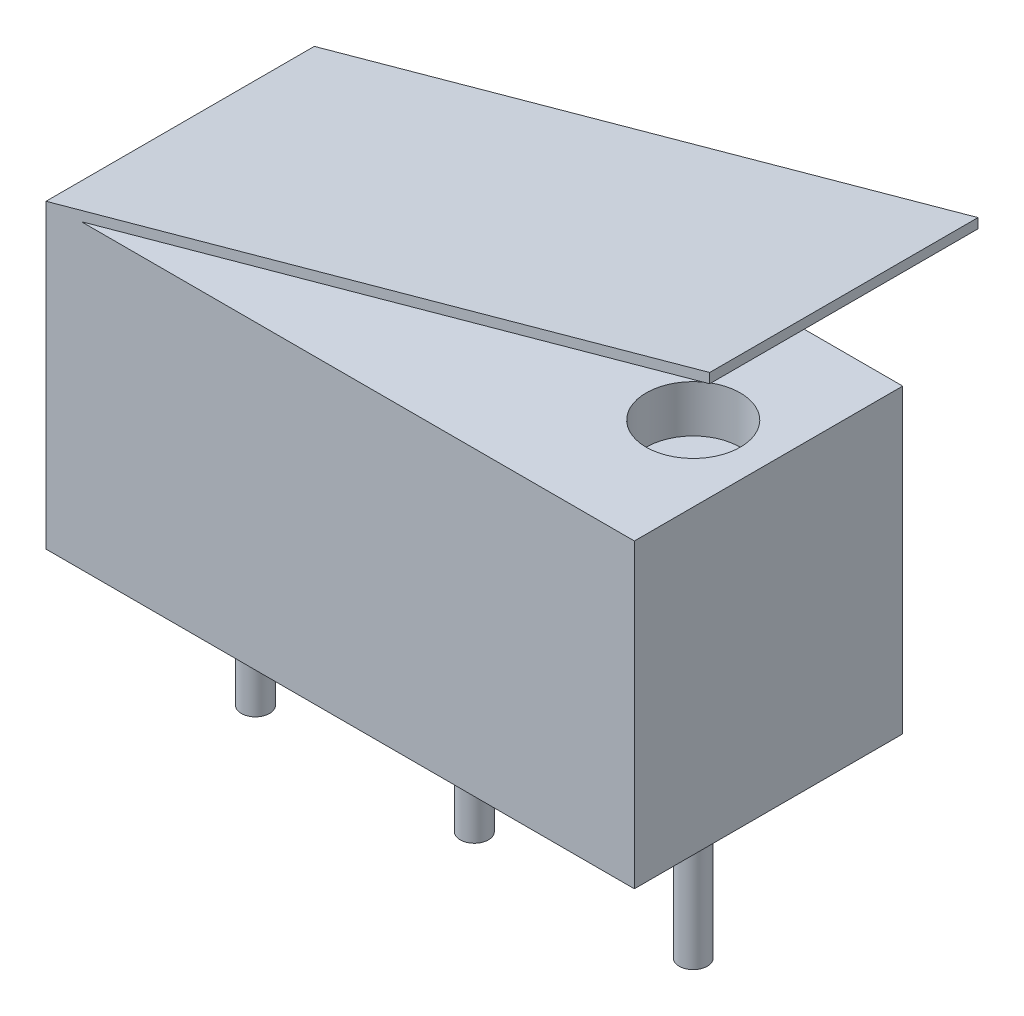
SolidWorks part; units mm, degrees
ref_plane "Front" through (0, 0, 0) normal (0, 0, 1) x (1, 0, 0)
ref_plane "Top" through (0, 0, 0) normal (0, 1, 0) x (1, 0, 0)
ref_plane "Right" through (0, 0, 0) normal (1, 0, 0) x (0, 0, -1)
sketch "Sketch1" plane through (0, 0, 0) normal (0, 1, 0) x (1, 0, 0)
  line L1 (-5.1136, 3.3562) -> (7.3864, 3.3562)
  line L2 (-5.1136, 3.3562) -> (-5.1136, -2.3438)
  line L3 (-5.1136, -2.3438) -> (7.3864, -2.3438)
  line L4 (7.3864, 3.3562) -> (7.3864, -2.3438)
  dimension "D1" = 12.5
  dimension "D2" = 5.7
  dimension "D3" = 7.3864
  dimension "D4" = 3.3562
extrude "Boss-Extrude1" add sketch "Sketch1" along normal blind 6.4
sketch "Sketch2" plane through (0, 0, 2.3438) normal (0, 0, 1) x (1, 0, 0)
  line L0 (-5.1136, 6.4) -> (8.9864, 10.3)
  line L2 (-5.1136, 6.4) -> (7.3864, 6.4) construction
  line L3 (-5.1136, 6.1925) -> (8.9864, 10.0925)
  line L4 (8.9864, 10.3) -> (8.9864, 10.0925)
  line L5 (-5.1136, 6.4) -> (-5.1136, 6.1925)
  line L7 (-5.0603, 6.2072) -> (9.0397, 10.1072) construction
  dimension "D1" = 14.1
  dimension "D2" = 10.3
  dimension "D3" = 0.2
extrude "Boss-Extrude2" add sketch "Sketch2" against normal up to surface (5.7 mm away) up to face at (1.1364, 3.2, -3.3562)
sketch "Sketch3" plane through (0, 0, 0) normal (0, -1, 0) x (1, 0, 0)
  line L0 (-5.1136, -3.3562) -> (-5.1136, 2.3438) construction
  line L1 (1.1364, 2.3438) -> (1.1364, -3.3562) construction
  line L2 (-5.1136, 2.3438) -> (7.3864, 2.3438) construction
  line L3 (7.3864, -3.3562) -> (-5.1136, -3.3562) construction
  circle A0 centre (-3.5136, -0.5062) radius 0.3
  circle A1 centre (1.1364, -0.5062) radius 0.3
  circle A2 centre (5.7864, -0.5062) radius 0.3
  point P2 (-5.1136, -0.5062)
  dimension "D1" = 0.6
  dimension "D2" = 1.6
extrude "Boss-Extrude3" add sketch "Sketch3" along normal offset from surface (3.5 mm away) 9.9 up to face at (1.5115, 6.4, -0.5062)
sketch "Sketch4" plane through (0, 6.4, 0) normal (0, 1, 0) x (1, 0, 0)
  circle A0 centre (5.7864, 0.5062) radius 1
  dimension "D1" = 2
extrude "Cut-Extrude1" cut sketch "Sketch4" against normal blind 1 contours A0
